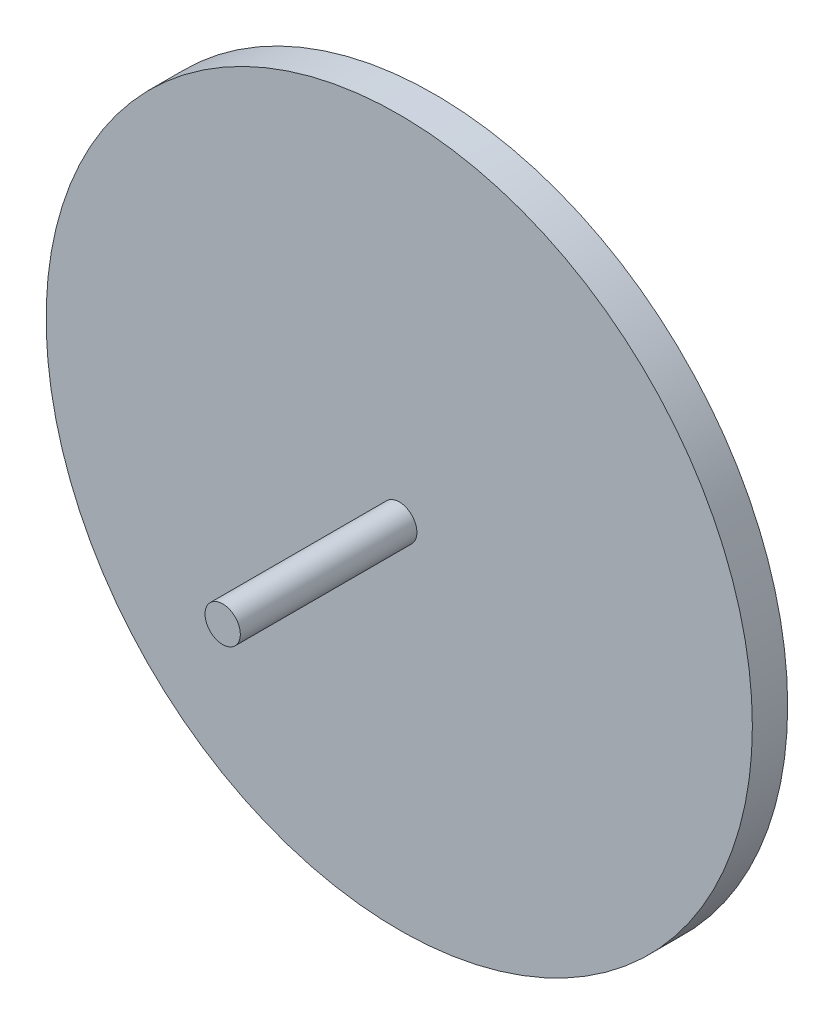
SolidWorks part; units mm, degrees
ref_plane "前基準面" through (0, 0, 0) normal (0, 0, 1) x (1, 0, 0)
ref_plane "上基準面" through (0, 0, 0) normal (0, 1, 0) x (1, 0, 0)
ref_plane "右基準面" through (0, 0, 0) normal (1, 0, 0) x (0, 0, -1)
sketch "草圖1" plane through (0, 0, 0) normal (0, 0, 1) x (1, 0, 0)
  circle A0 centre (0, 0) radius 50
  dimension "D1" = 100
extrude "填料-伸長1" add sketch "草圖1" along normal blind 5
sketch "草圖2" plane through (0, 0, 5) normal (0, 0, 1) x (1, 0, 0)
  circle A0 centre (0, 0) radius 2.5
  dimension "D1" = 5
extrude "填料-伸長2" add sketch "草圖2" along normal blind 25
